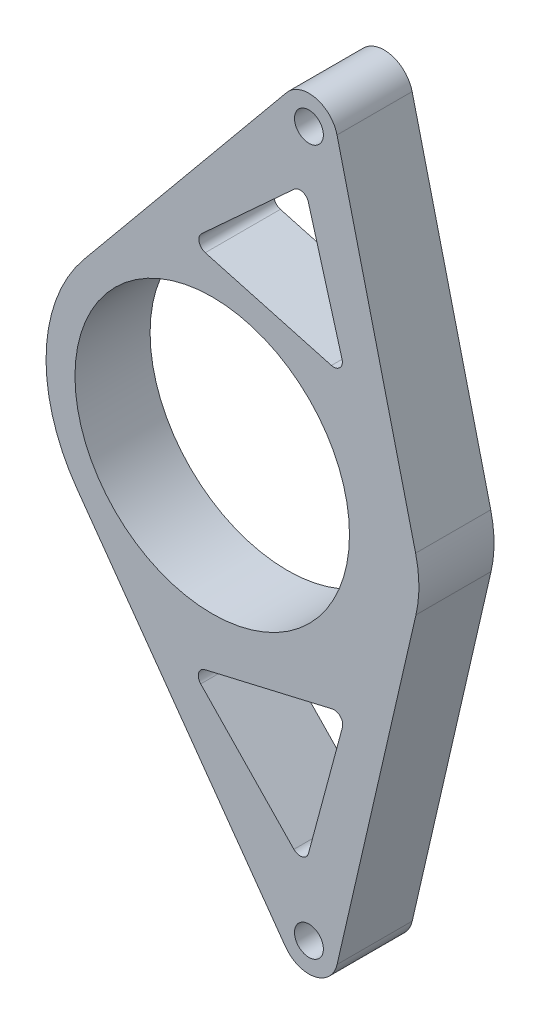
SolidWorks part; units mm, degrees
material "1023 Carbon Steel Sheet (SS)"
ref_plane "Front Plane" through (0, 0, 0) normal (0, 0, 1) x (1, 0, 0)
ref_plane "Top Plane" through (0, 0, 0) normal (0, 1, 0) x (1, 0, 0)
ref_plane "Right Plane" through (0, 0, 0) normal (1, 0, 0) x (0, 0, -1)
sketch "Sketch2" plane through (0, 0, 0) normal (0, 0, 1) x (1, 0, 0)
  line L0 (-44.3614, 36.583) -> (25.7498, 121.6016)
  line L1 (-46.8128, -33.3888) -> (25.3235, -134.5278)
  line L2 (43.2094, -130.9668) -> (70.4954, -12.5699)
  line L3 (70.382, 5.8749) -> (43.1811, 117.6048)
  line L4 (33.4649, 115.2393) -> (-221.8046, 115.2393) construction
  line L5 (33.4649, -128.721) -> (-210.4722, -128.721) construction
  line L6 (0, 0) -> (33.4649, 115.2393) construction
  line L7 (0, 0) -> (33.4649, -128.721) construction
  circle A0 centre (0, 0) radius 47.5
  arc A1 (-44.3614, 36.583) -> (-46.8128, -33.3888) centre (0, 0) ccw
  circle A2 centre (33.4649, 115.2393) radius 5
  arc A3 (43.1811, 117.6048) -> (25.7498, 121.6016) centre (33.4649, 115.2393) ccw
  arc A4 (25.3235, -134.5278) -> (43.2094, -130.9668) centre (33.4649, -128.721) ccw
  circle A5 centre (33.4649, -128.721) radius 5
  arc A6 (70.4954, -12.5699) -> (70.382, 5.8749) centre (31.5172, -3.5869) ccw
  point P23 (71.8123, 0)
  dimension "D1" = 95
  dimension "D2" = 120
  dimension "D3" = 20
  dimension "D4" = 20
  dimension "D5" = 10
  dimension "D9" = 115
  dimension "D8" = 40
  dimension "D6" = 133
  dimension "D7" = 73.807
extrude "Boss-Extrude2" add sketch "Sketch2" along normal blind 26
sketch "Sketch3" plane through (0, 0, 0) normal (0, 0, -1) x (-1, 0, 0)
  line L0 (-33.26, 92.5333) -> (-44.9203, 51.2737)
  line L1 (-41.2407, 47.5645) -> (2.4107, 59.5238)
  line L2 (3.6442, 64.6295) -> (-28.3469, 93.9297)
  line L3 (-41.4869, -55.2392) -> (2.5037, -65.4836)
  line L4 (3.9832, -70.4875) -> (-28.2565, -103.9324)
  line L5 (-33.3135, -102.6296) -> (-45.0644, -58.9403)
  arc A0 (3.9832, -70.4875) -> (2.5037, -65.4836) centre (1.8233, -68.4054) ccw
  arc A1 (-28.2565, -103.9324) -> (-33.3135, -102.6296) centre (-30.4164, -101.8504) cw
  arc A2 (-45.0644, -58.9403) -> (-41.4869, -55.2392) centre (-42.1673, -58.1611) cw
  arc A3 (2.4107, 59.5238) -> (3.6442, 64.6295) centre (1.618, 62.4172) ccw
  arc A4 (-41.2407, 47.5645) -> (-44.9203, 51.2737) centre (-42.0334, 50.4579) cw
  arc A5 (-33.26, 92.5333) -> (-28.3469, 93.9297) centre (-30.3731, 91.7174) cw
  point P5 (-31.9363, -107.7497)
  dimension "D1" = 3
extrude "Cut-Extrude1" cut sketch "Sketch3" against normal up to surface (26 mm away) up to face at (47.5, 0, 26)
